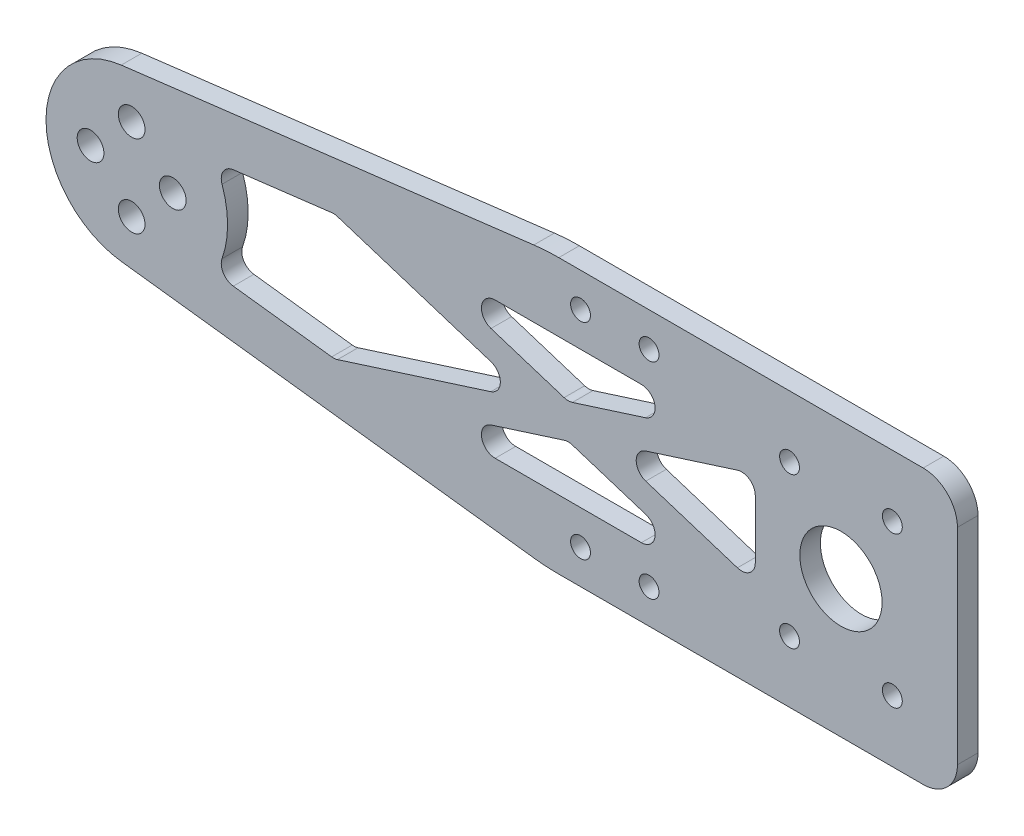
SolidWorks part; units mm, degrees
material "Thornel Mat VMA"
ref_plane "前视基准面" through (0, 0, 0) normal (0, 0, 1) x (1, 0, 0)
ref_plane "上视基准面" through (0, 0, 0) normal (0, 1, 0) x (1, 0, 0)
ref_plane "右视基准面" through (0, 0, 0) normal (1, 0, 0) x (0, 0, -1)
other "Configuration Table"
sketch "草图1" plane through (0, 0, 0) normal (0, 0, 1) x (1, 0, 0)
  line L0 (0, 0) -> (120.5, 0) construction
  line L1 (60.5, 20) -> (120.5, 20)
  line L3 (60.5, -20) -> (120.5, -20)
  line L4 (120.5, 20) -> (120.5, -20)
  line L5 (60.5, 20) -> (60.5, -20) construction
  line L6 (60.5, 20) -> (-1.519, 12.4074)
  line L7 (-1.519, -12.4074) -> (60.5, -20)
  arc A0 (-1.519, 12.4074) -> (-1.519, -12.4074) centre (0, 0) ccw
  point P1 (60.5, -20)
  point P10 (60.5, 20)
  dimension "D2" = 12.5
  dimension "D1" = 120.5
  dimension "D3" = 40
  dimension "D4" = 60
extrude "凸台-拉伸1" add sketch "草图1" along normal blind 3
sketch "草图2" plane through (0, 0, 3) normal (0, 0, 1) x (1, 0, 0)
  circle A0 centre (0, 0) radius 6 construction
  circle A1 centre (0, 6) radius 1.95
  circle A2 centre (6, 0) radius 1.95
  circle A3 centre (0, -6) radius 1.95
  circle A4 centre (-6, 0) radius 1.95
  point P13 (0, 0)
  dimension "D1" = 12
  dimension "D2" = 3.9
  dimension "D3" = 4
extrude "切除-拉伸1" cut sketch "草图2" against normal through all and the other way through all
fillet "圆角1" radius 5 2 edges at (120.5, -20, 1.5) (120.5, 20, 1.5)
sketch "草图3" plane through (0, 0, 0) normal (0, 0, -1) x (-1, 0, 0)
  line L0 (-120.5, -15) -> (-120.5, 15) construction
  line L1 (-60.5, -20) -> (-115.5, -20) construction
  circle A0 centre (-111, -11) radius 1.45
  circle A1 centre (-111, 11) radius 1.45
  circle A2 centre (-96, 11) radius 1.45
  circle A3 centre (-96, -11) radius 1.45
  dimension "D1" = 2.9
  dimension "D3" = 22
  dimension "D4" = 9.5
  dimension "D5" = 9
  dimension "D2" = 15
extrude "切除-拉伸2" cut sketch "草图3" against normal through all
sketch "草图4" plane through (0, 0, 3) normal (0, 0, 1) x (1, 0, 0)
  line L0 (120.5, 15) -> (-1.2438, 15) construction
  line L1 (120.5, -15) -> (120.5, 15) construction
  line L2 (120.5, 0) -> (45.471, 0) construction
  line L3 (115.5, 20) -> (60.5, 20) construction
  circle A0 centre (75.5, 15) radius 1.45
  circle A1 centre (65.5, 15) radius 1.45
  circle A2 centre (65.5, -15) radius 1.45
  circle A3 centre (75.5, -15) radius 1.45
  dimension "D2" = 2.9
  dimension "D3" = 10
  dimension "D1" = 5
  dimension "D4" = 45
extrude "切除-拉伸3" cut sketch "草图4" against normal through all
sketch "草图6" plane through (0, 0, 3) normal (0, 0, 1) x (1, 0, 0)
  line L0 (12.1106, 7.0237) -> (36.422, 10) construction
  line L1 (36.422, 10) -> (91, 10) construction
  line L2 (91, 10) -> (91, -10) construction
  line L3 (91, -10) -> (36.422, -10) construction
  line L4 (36.422, -10) -> (12.1106, -7.0237) construction
  line L5 (-1.519, -12.4074) -> (60.5, -20) construction
  line L6 (12.1106, 7.0237) -> (29.6219, 9.1675)
  line L7 (60.5, 20) -> (-1.519, 12.4074) construction
  line L9 (91, 7) -> (69.039, 0) construction
  line L10 (69.039, 0) -> (91, -7) construction
  line L11 (40.1813, 10) -> (63.711, 2.5) construction
  line L12 (63.711, -2.5) -> (87.2406, -10) construction
  line L13 (40.1813, -10) -> (63.711, -2.5) construction
  line L14 (63.711, 2.5) -> (87.2406, 10) construction
  line L15 (58.383, 0) -> (29.6219, 9.1675) construction
  line L16 (58.383, 0) -> (69.039, 0) construction
  line L17 (58.383, 0) -> (29.6219, -9.1675) construction
  line L18 (63.711, 2.5) -> (63.711, -2.5) construction
  line L19 (29.6219, 9.1675) -> (58.383, 0)
  line L20 (58.383, 0) -> (29.6219, -9.1675)
  line L21 (29.6219, -9.1675) -> (12.1106, -7.0237)
  line L22 (40.1813, -10) -> (63.711, -2.5)
  line L23 (63.711, -2.5) -> (87.2406, -10)
  line L24 (87.2406, -10) -> (40.1813, -10)
  line L25 (40.1813, 10) -> (63.711, 2.5)
  line L26 (63.711, 2.5) -> (87.2406, 10)
  line L27 (87.2406, 10) -> (40.1813, 10)
  line L28 (91, 7) -> (69.039, 0)
  line L29 (69.039, 0) -> (91, -7)
  line L30 (91, -7) -> (91, 7)
  line L31 (60.5, 20) -> (-1.519, 12.4074) construction
  line L32 (96, 11) -> (111, 11) construction
  circle A0 centre (0, 0) radius 12.5 construction
  arc A1 (-1.519, 12.4074) -> (-1.519, -12.4074) centre (0, 0) ccw construction
  arc A2 (12.1106, 7.0237) -> (12.1106, -7.0237) centre (0, 0) cw
  circle A3 centre (96, 11) radius 1.45 construction
  circle A4 centre (65.5, 15) radius 1.45 construction
  circle A5 centre (103.5, 0) radius 6
  point P10 (63.711, 0)
  point P34 (63.711, 10)
  point P38 (91, 0)
  point P39 (63.711, -10)
  point P43 (103.5, 11)
  dimension "D4" = 5
  dimension "D7" = 12
  dimension "D8" = 14
  dimension "D1" = 7
  dimension "D2" = 5
  dimension "D3" = 5
  dimension "D5" = 4
  dimension "D6" = 14
fillet "圆角2" radius 30 2 edges at (60.5, -20, 1.5) (60.5, 20, 1.5)
extrude "切除-拉伸4" cut sketch "草图6" against normal through all
fillet "圆角3" radius 2 14 edges at (29.6219, 9.1675, 1.5) (58.383, 0, 1.5) (29.6219, -9.1675, 1.5) (12.1106, -7.0237, 1.5) (12.1106, 7.0237, 1.5) (63.711, -2.5, 1.5) (87.2406, -10, 1.5) (69.039, 0, 1.5) (91, 7, 1.5) (91, -7, 1.5) (63.711, 2.5, 1.5) (40.1813, 10, 1.5) (87.2406, 10, 1.5) (40.1813, -10, 1.5)
